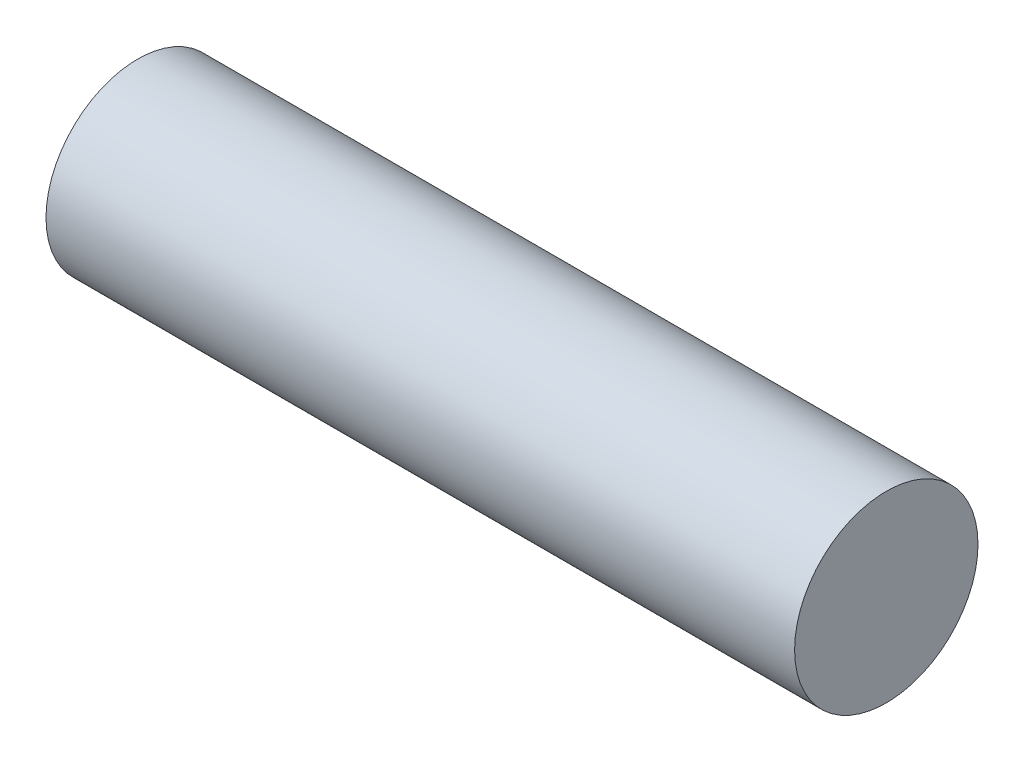
SolidWorks part; units mm, degrees
ref_plane "정면" through (0, 0, 0) normal (0, 0, 1) x (1, 0, 0)
ref_plane "윗면" through (0, 0, 0) normal (0, 1, 0) x (1, 0, 0)
ref_plane "우측면" through (0, 0, 0) normal (1, 0, 0) x (0, 0, -1)
sketch "Sketch1" plane through (0, 0, 0) normal (1, 0, 0) x (0, 0, -1)
  circle A0 centre (0, 0) radius 2.45
  dimension "D1" = 4.9
extrude "Boss-Extrude1" add sketch "Sketch1" along normal mid plane 20 contours A0
